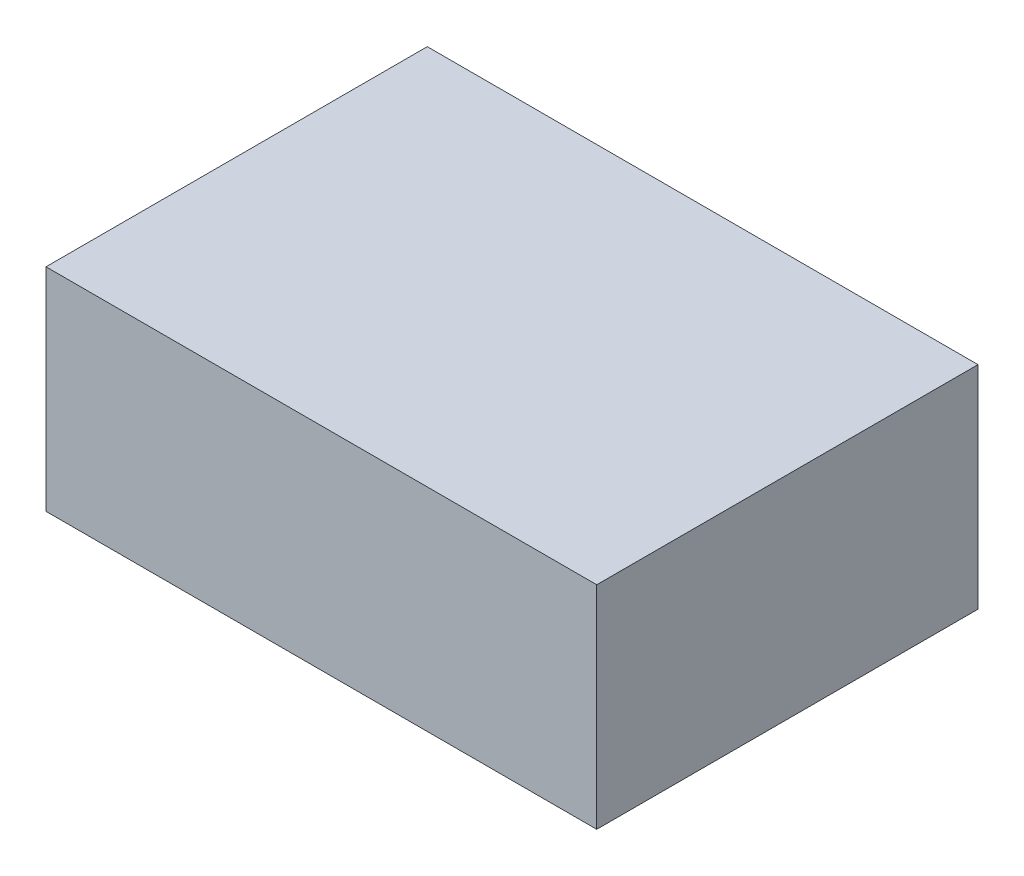
SolidWorks part; units mm, degrees
ref_plane "Спереди" through (0, 0, 0) normal (0, 0, 1) x (1, 0, 0)
ref_plane "Сверху" through (0, 0, 0) normal (0, 1, 0) x (1, 0, 0)
ref_plane "Справа" through (0, 0, 0) normal (1, 0, 0) x (0, 0, -1)
other "Configuration Table"
sketch "Эскиз1" plane through (0, 0, 0) normal (0, 1, 0) x (1, 0, 0)
  line L1 (32.5, -22.5) -> (-32.5, -22.5)
  line L2 (32.5, -22.5) -> (32.5, 22.5)
  line L3 (32.5, 22.5) -> (-32.5, 22.5)
  line L4 (-32.5, -22.5) -> (-32.5, 22.5)
  line L5 (32.5, -22.5) -> (-32.5, 22.5) construction
  line L6 (32.5, 22.5) -> (-32.5, -22.5) construction
  point P0 (0, 0)
extrude "Бобышка-Вытянуть1" add sketch "Эскиз1" along normal blind 25
sketch "Эскиз2" plane through (0, 0, 0) normal (0, -1, 0) x (1, 0, 0)
  circle A0 centre (-29.5, 13.5) radius 1.5
  circle A1 centre (29.5, 13.5) radius 1.5
  circle A2 centre (-29.5, -13.5) radius 1.5
  circle A3 centre (29.5, -13.5) radius 1.5
extrude "Вырез-Вытянуть1" cut sketch "Эскиз2" against normal blind 10
